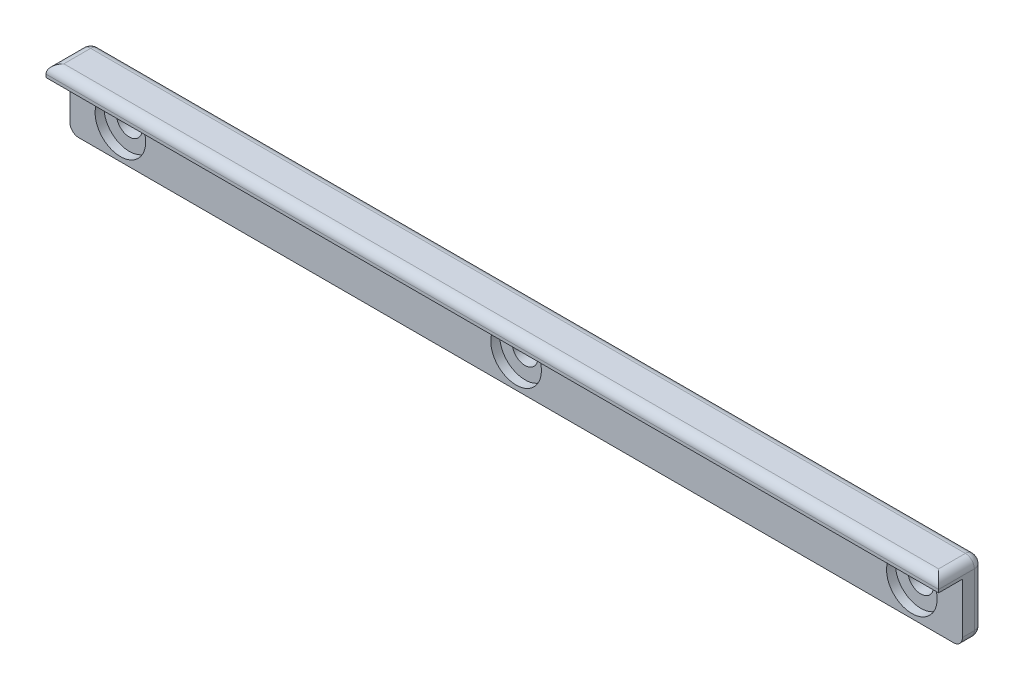
SolidWorks part; units mm, degrees
ref_plane "Front Plane" through (0, 0, 0) normal (0, 0, 1) x (1, 0, 0)
ref_plane "Top Plane" through (0, 0, 0) normal (0, 1, 0) x (1, 0, 0)
ref_plane "Right Plane" through (0, 0, 0) normal (1, 0, 0) x (0, 0, -1)
sketch "Sketch1" plane through (0, 0, 0) normal (0, 0, 1) x (1, 0, 0)
  line L0 (0, 0) -> (150, 0)
  line L1 (150, 0) -> (150, -10)
  line L2 (150, -10) -> (0, -10)
  line L3 (0, -10) -> (0, 0)
  line L4 (75, 0) -> (75, -10) construction
  line L5 (75, -5) -> (8.5, -5) construction
  line L6 (75, -5) -> (141.5, -5) construction
  circle A0 centre (75, -5) radius 4.25
  circle A1 centre (141.5, -5) radius 4.25
  circle A2 centre (8.5, -5) radius 4.25
  dimension "D5" = 8.5
  dimension "D6" = 8.5
  dimension "D7" = 8.5
  dimension "D1" = 150
  dimension "D2" = 10
  dimension "D3" = 66.5
  dimension "D4" = 66.5
extrude "Boss-Extrude1" add sketch "Sketch1" along normal blind 1.5
sketch "Sketch2" plane through (0, 0, 0) normal (0, 0, -1) x (-1, 0, 0)
  line L0 (0, 0) -> (0, -10)
  line L1 (0, -10) -> (-150, -10)
  line L2 (-150, -10) -> (-150, 0)
  line L3 (-150, 0) -> (0, 0)
  circle A0 centre (-8.5, -5) radius 2.15
  circle A1 centre (-75, -5) radius 2.15
  circle A2 centre (-141.5, -5) radius 2.15
  dimension "D1" = 4.3
  dimension "D2" = 4.3
  dimension "D3" = 4.3
extrude "Boss-Extrude2" add sketch "Sketch2" along normal blind 2
sketch "Sketch3" plane through (0, 0, 1.5) normal (0, 0, 1) x (1, 0, 0)
  line L0 (0, 0) -> (0, 2)
  line L1 (150, 0) -> (0, 0)
  line L2 (0, 2) -> (150, 2)
  line L3 (150, 2) -> (150, 0)
  dimension "D1" = 2
extrude "Boss-Extrude3" add sketch "Sketch3" along normal blind 4 and the other way blind 3.5
fillet "Fillet1" radius 1.5 9 edges at (0, -4, -2) (0, -10, -0.25) (75, -10, -2) (150, -10, -0.25) (150, -4, -2) (150, 2, 1.75) (0, 2, 1.75) (75, 2, 5.5) (75, 2, -2)
